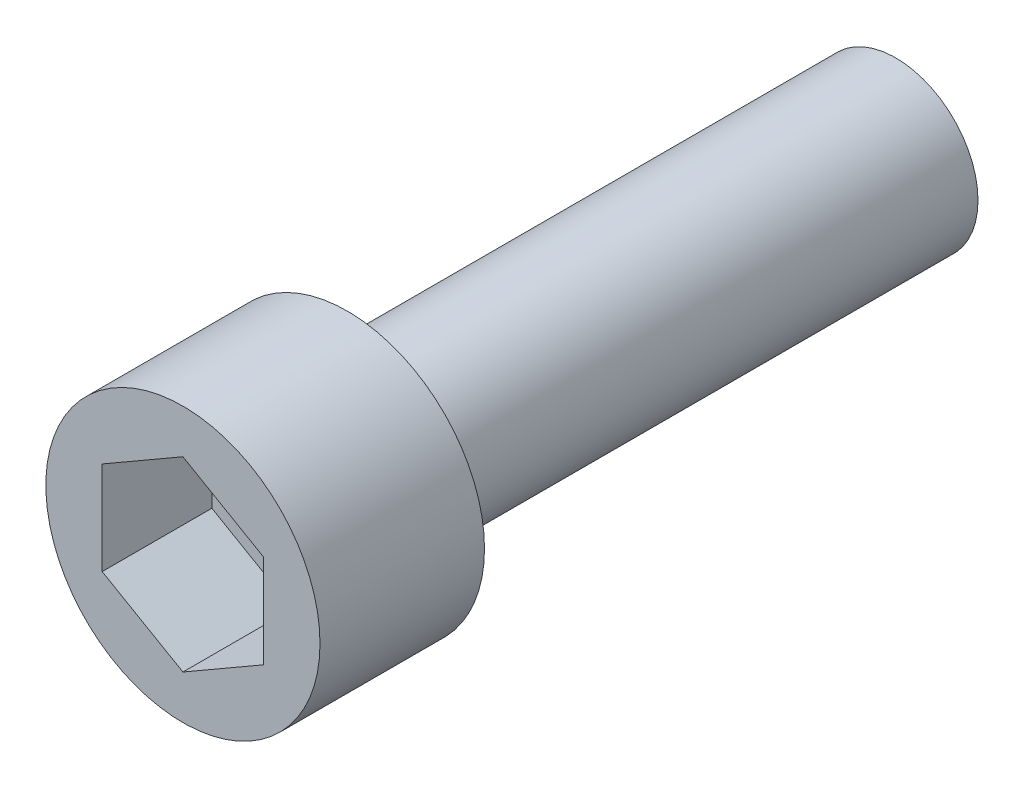
SolidWorks part; units mm, degrees
ref_plane "前视基准面" through (0, 0, 0) normal (0, 0, 1) x (1, 0, 0)
ref_plane "上视基准面" through (0, 0, 0) normal (0, 1, 0) x (1, 0, 0)
ref_plane "右视基准面" through (0, 0, 0) normal (1, 0, 0) x (0, 0, -1)
sketch "草图1" plane through (0, 0, 0) normal (0, 0, 1) x (1, 0, 0)
  circle A0 centre (0, 0) radius 1.5
  dimension "D1" = 3
extrude "凸台-拉伸1" add sketch "草图1" along normal blind 10
cosmetic thread "装饰螺纹线1" parameters "D2"=2.459
sketch "草图2" plane through (0, 0, 10) normal (0, 0, 1) x (1, 0, 0)
  circle A0 centre (0, 0) radius 2.5
  dimension "D1" = 5
extrude "凸台-拉伸2" add sketch "草图2" along normal blind 3
sketch "草图3" plane through (0, 0, 13) normal (0, 0, 1) x (1, 0, 0)
  line L1 (0, 1.7) -> (-1.4722, 0.85)
  line L2 (-1.4722, 0.85) -> (-1.4722, -0.85)
  line L3 (-1.4722, -0.85) -> (0, -1.7)
  line L4 (0, -1.7) -> (1.4722, -0.85)
  line L5 (1.4722, -0.85) -> (1.4722, 0.85)
  line L6 (1.4722, 0.85) -> (0, 1.7)
  circle A0 centre (0, 0) radius 1.4722 construction
  dimension "D1" = 1.7
extrude "切除-拉伸1" cut sketch "草图3" against normal blind 2
